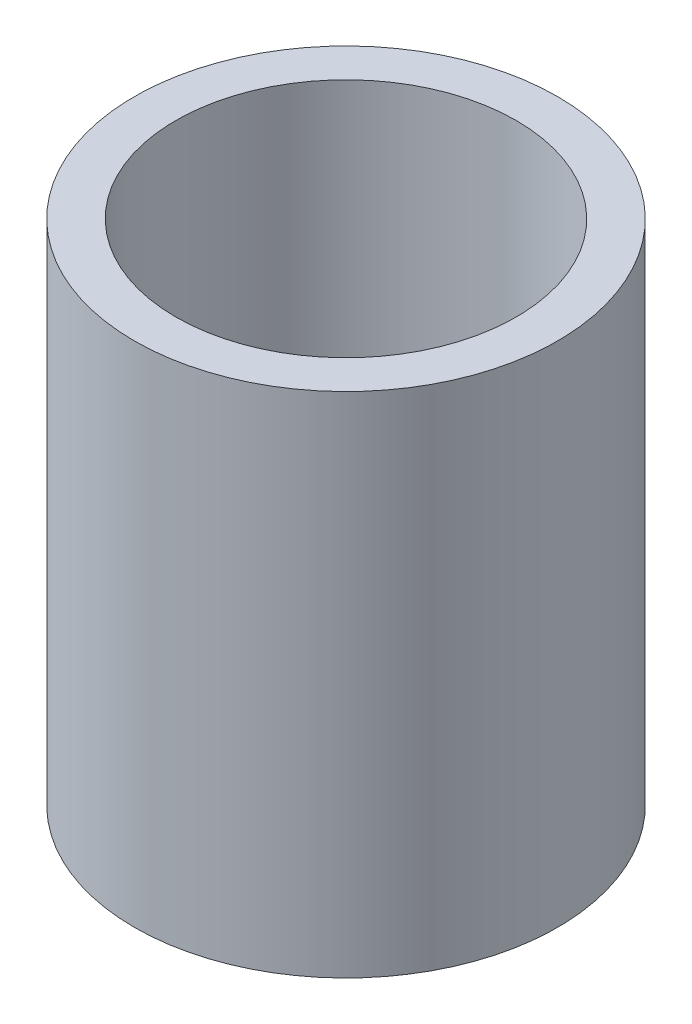
SolidWorks part; units mm, degrees
ref_plane "Front Plane" through (0, 0, 0) normal (0, 0, 1) x (1, 0, 0)
ref_plane "Top Plane" through (0, 0, 0) normal (0, 1, 0) x (1, 0, 0)
ref_plane "Right Plane" through (0, 0, 0) normal (1, 0, 0) x (0, 0, -1)
sketch "Sketch1" plane through (0, 0, 0) normal (0, 1, 0) x (1, 0, 0)
  circle A0 centre (0, 0) radius 12.7699
  circle A1 centre (0, 0) radius 15.875
  dimension "D1" = 25.5397
  dimension "D2" = 31.75
extrude "Extrude1" add sketch "Sketch1" along normal blind 38.1
